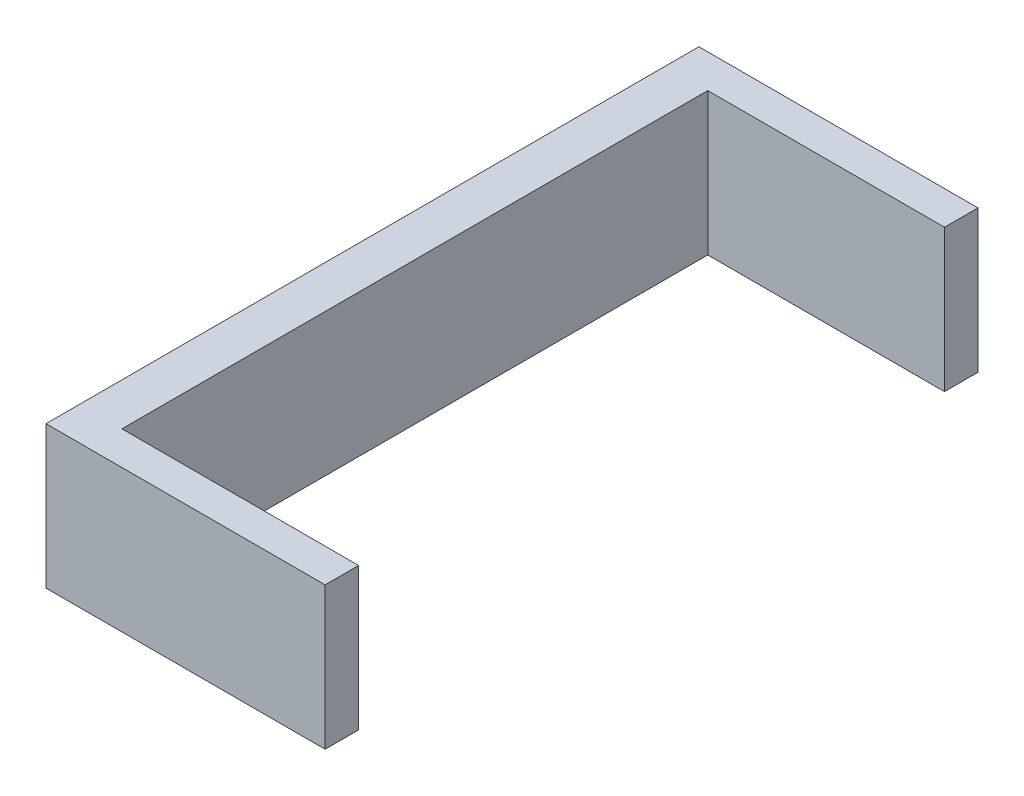
SolidWorks part; units mm, degrees
ref_plane "Front Plane" through (0, 0, 0) normal (0, 0, 1) x (1, 0, 0)
ref_plane "Top Plane" through (0, 0, 0) normal (0, 1, 0) x (1, 0, 0)
ref_plane "Right Plane" through (0, 0, 0) normal (1, 0, 0) x (0, 0, -1)
sketch "Sketch1" plane through (0, 0, 0) normal (0, 1, 0) x (1, 0, 0)
  line L1 (-16.0387, 65.6467) -> (0, 65.6467)
  line L2 (-16.0387, 65.6467) -> (-16.0387, -45.1321)
  line L4 (0, 65.6467) -> (0, -45.1321)
  line L5 (0, -45.1321) -> (89.5183, -45.1321)
  line L6 (-16.0387, -45.1321) -> (-16.0387, -57.8139)
  line L7 (-16.0387, -57.8139) -> (89.5183, -57.8139)
  line L8 (89.5183, -45.1321) -> (89.5183, -57.8139)
extrude "Boss-Extrude1" add sketch "Sketch1" along normal mid plane 53.848
mirror "Mirror1" about plane through (-16.0387, 26.924, -65.6467) normal (0, 0, 1) of "Boss-Extrude1"
